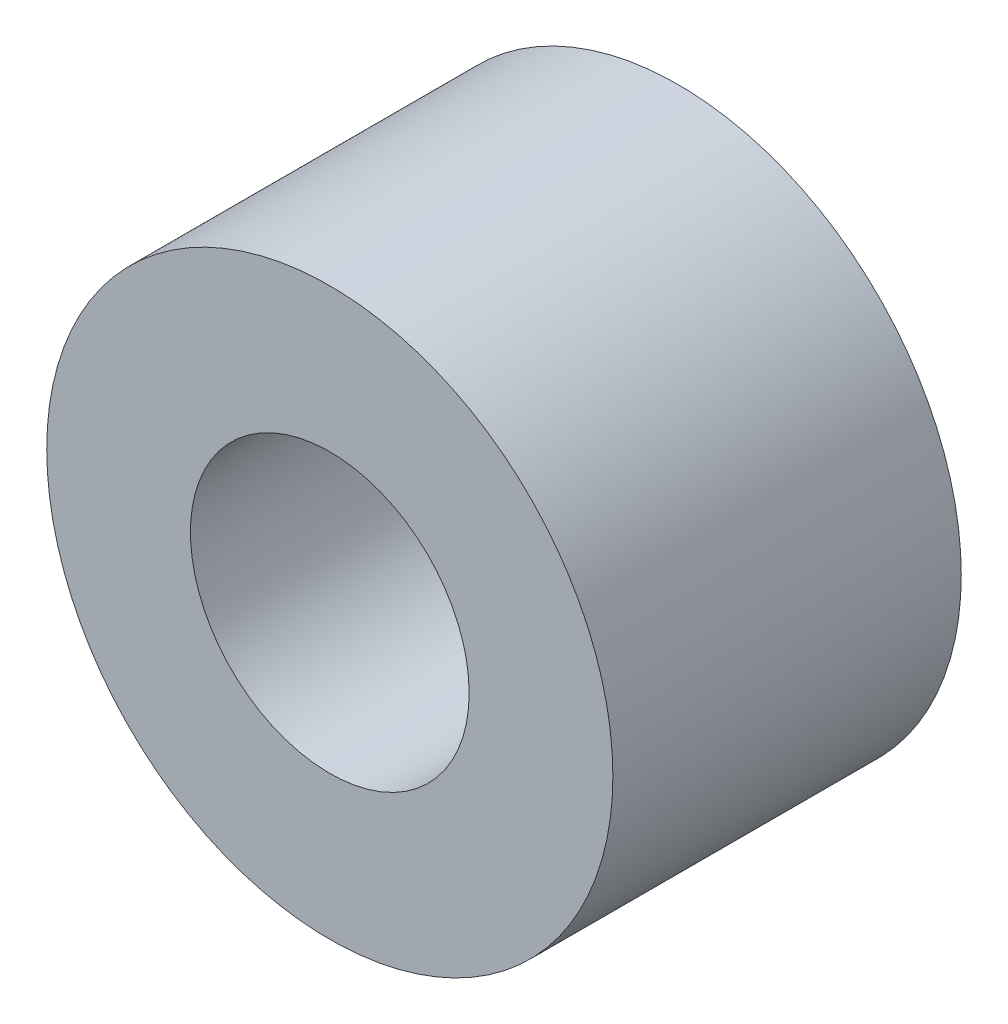
SolidWorks part; units mm, degrees
material "Nylon 101"
ref_plane "Front Plane" through (0, 0, 0) normal (0, 0, 1) x (1, 0, 0)
ref_plane "Top Plane" through (0, 0, 0) normal (0, 1, 0) x (1, 0, 0)
ref_plane "Right Plane" through (0, 0, 0) normal (1, 0, 0) x (0, 0, -1)
sketch "Sketch1" plane through (0, 0, 0) normal (0, 0, 1) x (1, 0, 0)
  circle A0 centre (0, 0) radius 3.25
  circle A1 centre (0, 0) radius 1.6
  dimension "D1" = 6.5
  dimension "D2" = 3.2
extrude "Boss-Extrude1" add sketch "Sketch1" along normal up to surface (4 mm away)
